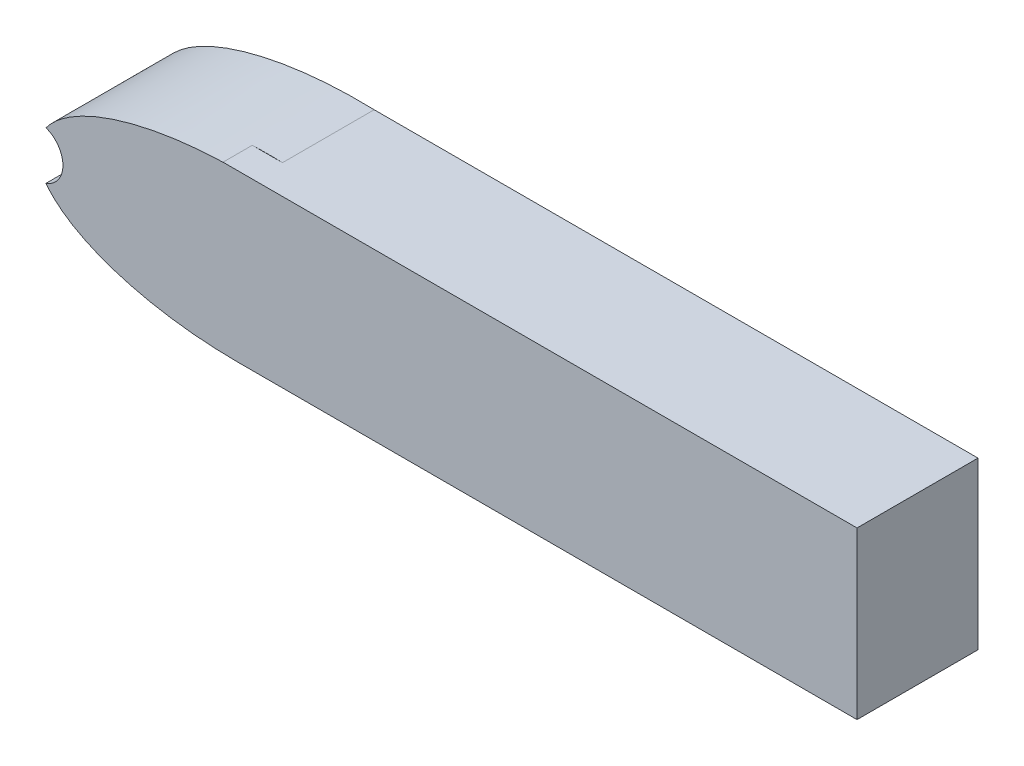
SolidWorks part; units mm, degrees
ref_plane "Front Plane" through (0, 0, 0) normal (0, 0, 1) x (1, 0, 0)
ref_plane "Top Plane" through (0, 0, 0) normal (0, 1, 0) x (1, 0, 0)
ref_plane "Right Plane" through (0, 0, 0) normal (1, 0, 0) x (0, 0, -1)
sketch "Sketch1" plane through (0, 0, 0) normal (0, 0, 1) x (1, 0, 0)
  line L0 (-74.443, 14.2388) -> (-14.8387, 14.2388)
  line L1 (-14.8387, 14.2388) -> (36.4872, 14.2388)
  line L2 (-14.8387, -18.8747) -> (-74.443, -18.8747)
  line L3 (36.4872, 14.2388) -> (36.4872, -18.8747)
  line L4 (36.4872, -18.8747) -> (-14.8387, -18.8747)
  ellipse E0 centre (-74.443, -2.3179) end of major axis (-114.5103, -2.3179) minor radius 16.5567
extrude "Boss-Extrude1" add sketch "Sketch1" along normal blind 18.288 contours E0
sketch "Sketch3" plane through (0, 0, 0) normal (0, 0, -1) x (-1, 0, 0)
  line L0 (74.443, -18.8747) -> (-48.9614, -18.8747)
  line L1 (-48.9614, -18.8747) -> (-48.9614, 14.2388)
  line L2 (-48.9614, 14.2388) -> (77.4907, 14.1908)
  ellipse E0 centre (74.443, -2.3179) end of major axis (114.5103, -2.3179) minor radius 16.5567 construction
  ellipse E2 centre (74.443, -2.3179) end of major axis (114.5103, -2.3179) minor radius 16.5567
  ellipse E3 centre (74.443, -2.3179) end of major axis (114.5103, -2.3179) minor radius 16.5567 (74.443, -18.8747) -> (77.4907, 14.1908) ccw
  dimension "D1" = 0
extrude "Boss-Extrude2" add sketch "Sketch3" against normal blind 24.13
sketch "Sketch4" plane through (0, 0, 0) normal (0, 0, -1) x (-1, 0, 0)
  circle A0 centre (114.5103, -2.3179) radius 5.0893
  ellipse E0 centre (74.443, -2.3179) end of major axis (114.5103, -2.3179) minor radius 16.5567 (74.443, -18.8747) -> (71.4686, 14.1931) ccw construction
extrude "Cut-Extrude1" cut sketch "Sketch4" against normal blind 49.784
sketch "Sketch5" plane through (0, 0, 0) normal (0, 0, -1) x (-1, 0, 0)
  arc A0 (112.7956, 2.4738) -> (112.7956, -7.1097) centre (114.5103, -2.3179) ccw construction
  ellipse E0 centre (74.443, -2.3179) end of major axis (109.421, -2.3179) minor radius 11.087
